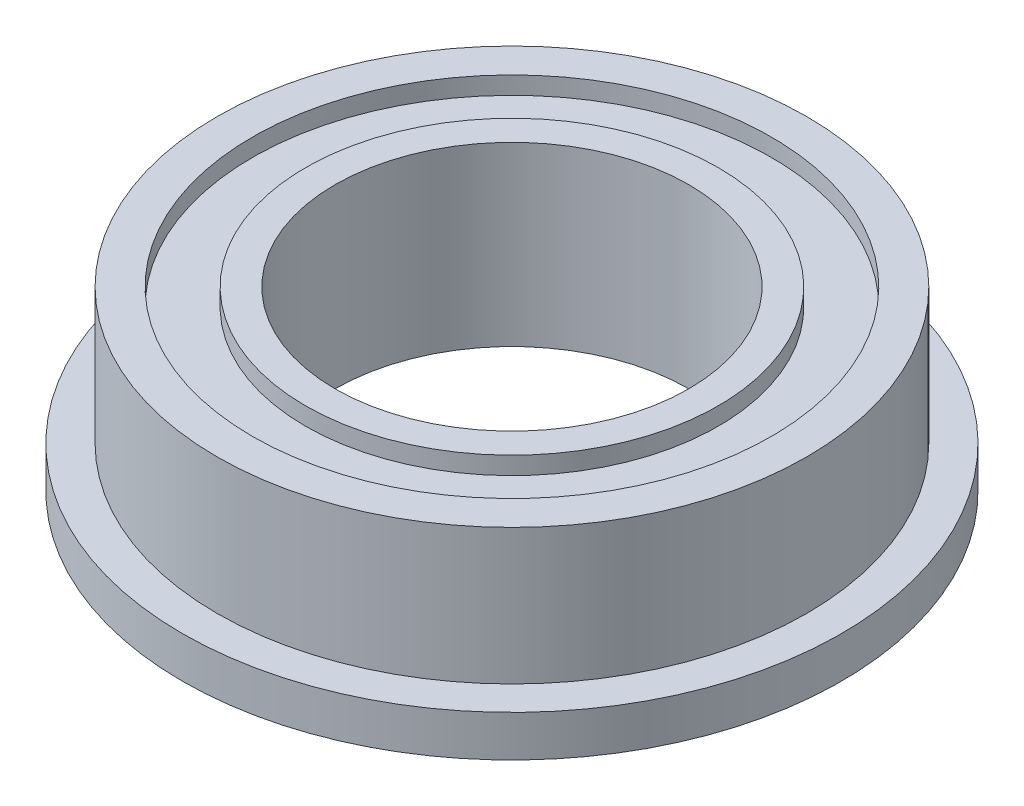
SolidWorks part; units mm, degrees
ref_plane "Front Plane" through (0, 0, 0) normal (0, 0, 1) x (1, 0, 0)
ref_plane "Top Plane" through (0, 0, 0) normal (0, 1, 0) x (1, 0, 0)
ref_plane "Right Plane" through (0, 0, 0) normal (1, 0, 0) x (0, 0, -1)
sketch "Sketch1" plane through (0, 0, 0) normal (0, 1, 0) x (1, 0, 0)
  circle A0 centre (0, 0) radius 5
  circle A1 centre (0, 0) radius 3
  dimension "D1" = 10
  dimension "D2" = 6
extrude "Boss-Extrude1" add sketch "Sketch1" along normal blind 3
sketch "Sketch2" plane through (0, 0, 0) normal (0, 1, 0) x (1, 0, 0)
  circle A0 centre (0, 0) radius 5
  circle A1 centre (0, 0) radius 5.59
  dimension "D1" = 11.18
extrude "Boss-Extrude2" add sketch "Sketch2" along normal blind 0.7
sketch "Sketch3" plane through (0, 3, 0) normal (0, 1, 0) x (1, 0, 0)
  circle A0 centre (0, 0) radius 3.5
  circle A1 centre (0, 0) radius 4.4
  dimension "D1" = 7
  dimension "D2" = 8.8
extrude "Cut-Extrude1" cut sketch "Sketch3" against normal blind 0.3
sketch "Sketch4" plane through (0, 0, 0) normal (0, 1, 0) x (1, 0, 0)
  circle A0 centre (0, 0) radius 3.5
  circle A1 centre (0, 0) radius 4.4
extrude "Cut-Extrude2" cut sketch "Sketch4" along normal blind 0.3
